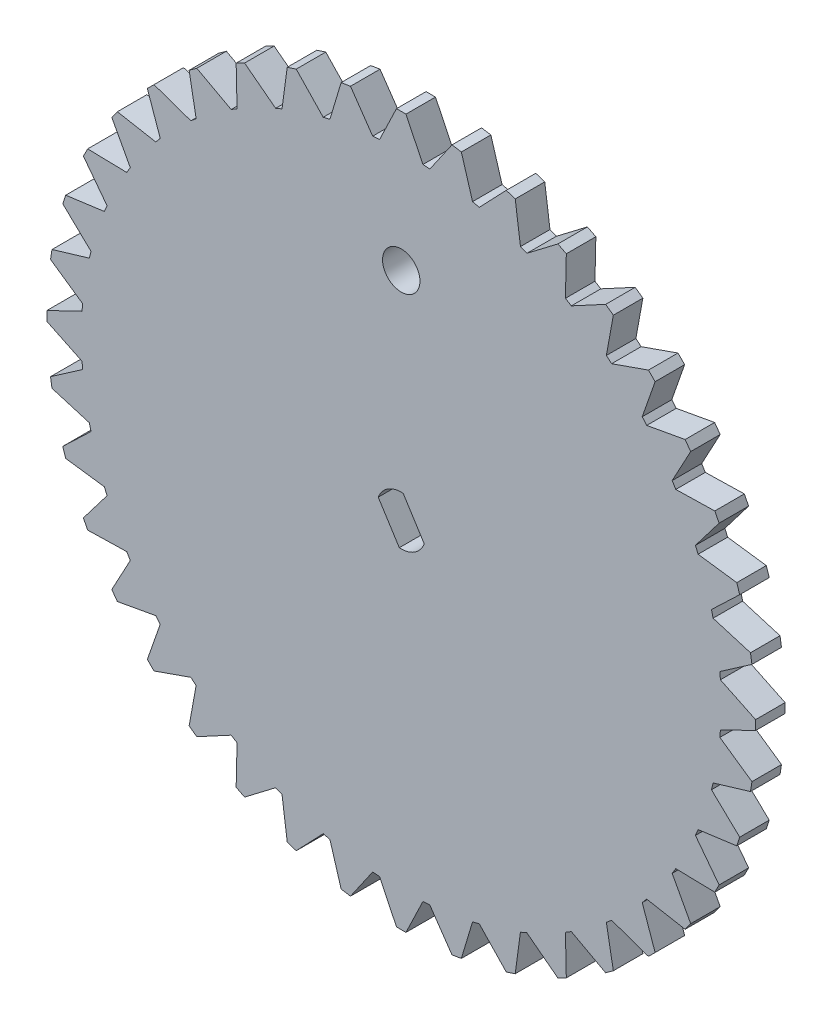
SolidWorks part; units mm, degrees
ref_plane "Front Plane" through (0, 0, 0) normal (0, 0, 1) x (1, 0, 0)
ref_plane "Top Plane" through (0, 0, 0) normal (0, 1, 0) x (1, 0, 0)
ref_plane "Right Plane" through (0, 0, 0) normal (1, 0, 0) x (0, 0, -1)
sketch "Sketch1" plane through (0, 0, 0) normal (0, 0, 1) x (1, 0, 0)
  circle A0 centre (0, 0) radius 32.5
  dimension "D1" = 65
extrude "Boss-Extrude1" add sketch "Sketch1" along normal blind 3
sketch "Sketch2" plane through (0, 0, 3) normal (0, 0, 1) x (1, 0, 0)
  line L210 (0, 37) -> (0, 27.9373) construction
  line L360 (-0.4809, 36) -> (-2.2, 32.4255)
  line L361 (0.4809, 36) -> (2.2, 32.4255)
  line L362 (2.2, 32.4255) -> (-2.2, 32.4255)
  line L489 (-0.4809, 36) -> (0.4809, 36)
  line L690 (6.1066, 35.4815) -> (7.2454, 31.6821)
  line L691 (7.2454, 31.6821) -> (2.8995, 32.3704)
  line L692 (5.1566, 35.632) -> (2.8995, 32.3704)
  line L693 (5.1566, 35.632) -> (6.1066, 35.4815)
  line L694 (11.582, 34.0894) -> (12.1123, 30.1586)
  line L695 (12.1123, 30.1586) -> (7.9277, 31.5183)
  line L696 (10.6672, 34.3866) -> (7.9277, 31.5183)
  line L697 (10.6672, 34.3866) -> (11.582, 34.0894)
  line L698 (16.7722, 31.8579) -> (16.6811, 27.8925)
  line L699 (16.6811, 27.8925) -> (12.7606, 29.8901)
  line L700 (15.9152, 32.2946) -> (12.7606, 29.8901)
  line L701 (15.9152, 32.2946) -> (16.7722, 31.8579)
  line L702 (21.5493, 28.8419) -> (20.839, 24.9396)
  line L703 (20.839, 24.9396) -> (17.2794, 27.5259)
  line L704 (20.7712, 29.4073) -> (17.2794, 27.5259)
  line L705 (20.7712, 29.4073) -> (21.5493, 28.8419)
  line L706 (25.7959, 25.1158) -> (24.4839, 21.3726)
  line L707 (24.4839, 21.3726) -> (21.3726, 24.4839)
  line L708 (25.1158, 25.7959) -> (21.3726, 24.4839)
  line L709 (25.1158, 25.7959) -> (25.7959, 25.1158)
  line L710 (29.4073, 20.7712) -> (27.5259, 17.2794)
  line L711 (27.5259, 17.2794) -> (24.9396, 20.839)
  line L712 (28.8419, 21.5493) -> (24.9396, 20.839)
  line L713 (28.8419, 21.5493) -> (29.4073, 20.7712)
  line L714 (32.2946, 15.9152) -> (29.8901, 12.7606)
  line L715 (29.8901, 12.7606) -> (27.8925, 16.6811)
  line L716 (31.8579, 16.7722) -> (27.8925, 16.6811)
  line L717 (31.8579, 16.7722) -> (32.2946, 15.9152)
  line L718 (34.3866, 10.6672) -> (31.5183, 7.9277)
  line L719 (31.5183, 7.9277) -> (30.1586, 12.1123)
  line L720 (34.0894, 11.582) -> (30.1586, 12.1123)
  line L721 (34.0894, 11.582) -> (34.3866, 10.6672)
  line L722 (35.632, 5.1566) -> (32.3704, 2.8995)
  line L723 (32.3704, 2.8995) -> (31.6821, 7.2454)
  line L724 (35.4815, 6.1066) -> (31.6821, 7.2454)
  line L725 (35.4815, 6.1066) -> (35.632, 5.1566)
  line L726 (36, -0.4809) -> (32.4255, -2.2)
  line L727 (32.4255, -2.2) -> (32.4255, 2.2)
  line L728 (36, 0.4809) -> (32.4255, 2.2)
  line L729 (36, 0.4809) -> (36, -0.4809)
  line L730 (35.4815, -6.1066) -> (31.6821, -7.2454)
  line L731 (31.6821, -7.2454) -> (32.3704, -2.8995)
  line L732 (35.632, -5.1566) -> (32.3704, -2.8995)
  line L733 (35.632, -5.1566) -> (35.4815, -6.1066)
  line L734 (34.0894, -11.582) -> (30.1586, -12.1123)
  line L735 (30.1586, -12.1123) -> (31.5183, -7.9277)
  line L736 (34.3866, -10.6672) -> (31.5183, -7.9277)
  line L737 (34.3866, -10.6672) -> (34.0894, -11.582)
  line L738 (31.8579, -16.7722) -> (27.8925, -16.6811)
  line L739 (27.8925, -16.6811) -> (29.8901, -12.7606)
  line L740 (32.2946, -15.9152) -> (29.8901, -12.7606)
  line L741 (32.2946, -15.9152) -> (31.8579, -16.7722)
  line L742 (28.8419, -21.5493) -> (24.9396, -20.839)
  line L743 (24.9396, -20.839) -> (27.5259, -17.2794)
  line L744 (29.4073, -20.7712) -> (27.5259, -17.2794)
  line L745 (29.4073, -20.7712) -> (28.8419, -21.5493)
  line L746 (25.1158, -25.7959) -> (21.3726, -24.4839)
  line L747 (21.3726, -24.4839) -> (24.4839, -21.3726)
  line L748 (25.7959, -25.1158) -> (24.4839, -21.3726)
  line L749 (25.7959, -25.1158) -> (25.1158, -25.7959)
  line L750 (20.7712, -29.4073) -> (17.2794, -27.5259)
  line L751 (17.2794, -27.5259) -> (20.839, -24.9396)
  line L752 (21.5493, -28.8419) -> (20.839, -24.9396)
  line L753 (21.5493, -28.8419) -> (20.7712, -29.4073)
  line L754 (15.9152, -32.2946) -> (12.7606, -29.8901)
  line L755 (12.7606, -29.8901) -> (16.6811, -27.8925)
  line L756 (16.7722, -31.8579) -> (16.6811, -27.8925)
  line L757 (16.7722, -31.8579) -> (15.9152, -32.2946)
  line L758 (10.6672, -34.3866) -> (7.9277, -31.5183)
  line L759 (7.9277, -31.5183) -> (12.1123, -30.1586)
  line L760 (11.582, -34.0894) -> (12.1123, -30.1586)
  line L761 (11.582, -34.0894) -> (10.6672, -34.3866)
  line L762 (5.1566, -35.632) -> (2.8995, -32.3704)
  line L763 (2.8995, -32.3704) -> (7.2454, -31.6821)
  line L764 (6.1066, -35.4815) -> (7.2454, -31.6821)
  line L765 (6.1066, -35.4815) -> (5.1566, -35.632)
  line L766 (-0.4809, -36) -> (-2.2, -32.4255)
  line L767 (-2.2, -32.4255) -> (2.2, -32.4255)
  line L768 (0.4809, -36) -> (2.2, -32.4255)
  line L769 (0.4809, -36) -> (-0.4809, -36)
  line L770 (-6.1066, -35.4815) -> (-7.2454, -31.6821)
  line L771 (-7.2454, -31.6821) -> (-2.8995, -32.3704)
  line L772 (-5.1566, -35.632) -> (-2.8995, -32.3704)
  line L773 (-5.1566, -35.632) -> (-6.1066, -35.4815)
  line L774 (-11.582, -34.0894) -> (-12.1123, -30.1586)
  line L775 (-12.1123, -30.1586) -> (-7.9277, -31.5183)
  line L776 (-10.6672, -34.3866) -> (-7.9277, -31.5183)
  line L777 (-10.6672, -34.3866) -> (-11.582, -34.0894)
  line L778 (-16.7722, -31.8579) -> (-16.6811, -27.8925)
  line L779 (-16.6811, -27.8925) -> (-12.7606, -29.8901)
  line L780 (-15.9152, -32.2946) -> (-12.7606, -29.8901)
  line L781 (-15.9152, -32.2946) -> (-16.7722, -31.8579)
  line L782 (-21.5493, -28.8419) -> (-20.839, -24.9396)
  line L783 (-20.839, -24.9396) -> (-17.2794, -27.5259)
  line L784 (-20.7712, -29.4073) -> (-17.2794, -27.5259)
  line L785 (-20.7712, -29.4073) -> (-21.5493, -28.8419)
  line L786 (-25.7959, -25.1158) -> (-24.4839, -21.3726)
  line L787 (-24.4839, -21.3726) -> (-21.3726, -24.4839)
  line L788 (-25.1158, -25.7959) -> (-21.3726, -24.4839)
  line L789 (-25.1158, -25.7959) -> (-25.7959, -25.1158)
  line L790 (-29.4073, -20.7712) -> (-27.5259, -17.2794)
  line L791 (-27.5259, -17.2794) -> (-24.9396, -20.839)
  line L792 (-28.8419, -21.5493) -> (-24.9396, -20.839)
  line L793 (-28.8419, -21.5493) -> (-29.4073, -20.7712)
  line L794 (-32.2946, -15.9152) -> (-29.8901, -12.7606)
  line L795 (-29.8901, -12.7606) -> (-27.8925, -16.6811)
  line L796 (-31.8579, -16.7722) -> (-27.8925, -16.6811)
  line L797 (-31.8579, -16.7722) -> (-32.2946, -15.9152)
  line L798 (-34.3866, -10.6672) -> (-31.5183, -7.9277)
  line L799 (-31.5183, -7.9277) -> (-30.1586, -12.1123)
  line L800 (-34.0894, -11.582) -> (-30.1586, -12.1123)
  line L801 (-34.0894, -11.582) -> (-34.3866, -10.6672)
  line L802 (-35.632, -5.1566) -> (-32.3704, -2.8995)
  line L803 (-32.3704, -2.8995) -> (-31.6821, -7.2454)
  line L804 (-35.4815, -6.1066) -> (-31.6821, -7.2454)
  line L805 (-35.4815, -6.1066) -> (-35.632, -5.1566)
  line L806 (-36, 0.4809) -> (-32.4255, 2.2)
  line L807 (-32.4255, 2.2) -> (-32.4255, -2.2)
  line L808 (-36, -0.4809) -> (-32.4255, -2.2)
  line L809 (-36, -0.4809) -> (-36, 0.4809)
  line L810 (-35.4815, 6.1066) -> (-31.6821, 7.2454)
  line L811 (-31.6821, 7.2454) -> (-32.3704, 2.8995)
  line L812 (-35.632, 5.1566) -> (-32.3704, 2.8995)
  line L813 (-35.632, 5.1566) -> (-35.4815, 6.1066)
  line L814 (-34.0894, 11.582) -> (-30.1586, 12.1123)
  line L815 (-30.1586, 12.1123) -> (-31.5183, 7.9277)
  line L816 (-34.3866, 10.6672) -> (-31.5183, 7.9277)
  line L817 (-34.3866, 10.6672) -> (-34.0894, 11.582)
  line L818 (-31.8579, 16.7722) -> (-27.8925, 16.6811)
  line L819 (-27.8925, 16.6811) -> (-29.8901, 12.7606)
  line L820 (-32.2946, 15.9152) -> (-29.8901, 12.7606)
  line L821 (-32.2946, 15.9152) -> (-31.8579, 16.7722)
  line L822 (-28.8419, 21.5493) -> (-24.9396, 20.839)
  line L823 (-24.9396, 20.839) -> (-27.5259, 17.2794)
  line L824 (-29.4073, 20.7712) -> (-27.5259, 17.2794)
  line L825 (-29.4073, 20.7712) -> (-28.8419, 21.5493)
  line L826 (-25.1158, 25.7959) -> (-21.3726, 24.4839)
  line L827 (-21.3726, 24.4839) -> (-24.4839, 21.3726)
  line L828 (-25.7959, 25.1158) -> (-24.4839, 21.3726)
  line L829 (-25.7959, 25.1158) -> (-25.1158, 25.7959)
  line L830 (-20.7712, 29.4073) -> (-17.2794, 27.5259)
  line L831 (-17.2794, 27.5259) -> (-20.839, 24.9396)
  line L832 (-21.5493, 28.8419) -> (-20.839, 24.9396)
  line L833 (-21.5493, 28.8419) -> (-20.7712, 29.4073)
  line L834 (-15.9152, 32.2946) -> (-12.7606, 29.8901)
  line L835 (-12.7606, 29.8901) -> (-16.6811, 27.8925)
  line L836 (-16.7722, 31.8579) -> (-16.6811, 27.8925)
  line L837 (-16.7722, 31.8579) -> (-15.9152, 32.2946)
  line L838 (-10.6672, 34.3866) -> (-7.9277, 31.5183)
  line L839 (-7.9277, 31.5183) -> (-12.1123, 30.1586)
  line L840 (-11.582, 34.0894) -> (-12.1123, 30.1586)
  line L841 (-11.582, 34.0894) -> (-10.6672, 34.3866)
  line L842 (-5.1566, 35.632) -> (-2.8995, 32.3704)
  line L843 (-2.8995, 32.3704) -> (-7.2454, 31.6821)
  line L844 (-6.1066, 35.4815) -> (-7.2454, 31.6821)
  line L845 (-6.1066, 35.4815) -> (-5.1566, 35.632)
  circle A5 centre (0, 0) radius 32.5 construction
  arc A6 (-32.9057, -16.918) -> (-36.778, 4.0467) centre (0, 0) ccw construction
  dimension "D4" = 2.2
  dimension "D5" = 1
  dimension "D3" = 2.2
  dimension "D2" = 37
extrude "Boss-Extrude6" add sketch "Sketch2" against normal up to surface (3 mm away) up to face at (32.5, 0, 0)
sketch "Sketch3" plane through (0, 0, 3) normal (0, 0, 1) x (1, 0, 0)
  line L7 (-2.337, 0.8878) -> (-0.198, -2.4921)
  line L8 (0.198, 2.4921) -> (2.337, -0.8878)
  line L9 (-0.198, -2.4921) -> (-2.337, 0.8878) construction
  circle A4 centre (0, 0) radius 2.5 construction
  arc A5 (0.198, 2.4921) -> (-2.337, 0.8878) centre (0, 0) ccw
  arc A6 (-0.198, -2.4921) -> (2.337, -0.8878) centre (0, 0) ccw
extrude "Cut-Extrude1" cut sketch "Sketch3" against normal up to surface (3 mm away) up to face at (0, 0, 0)
sketch "Sketch5" plane through (0, 0, 0) normal (0, 0, -1) x (-1, 0, 0)
  line L0 (-0.198, 2.4921) -> (-2.337, -0.8878)
  line L1 (0.198, -2.4921) -> (2.337, 0.8878)
  circle A0 centre (0, 0) radius 7
  arc A1 (2.337, 0.8878) -> (-0.198, 2.4921) centre (0, 0) ccw
  arc A2 (-2.337, -0.8878) -> (0.198, -2.4921) centre (0, 0) ccw
  dimension "D1" = 14
extrude "Boss-Extrude7" add sketch "Sketch5" along normal up to surface (3 mm away)
sketch "Sketch7" plane through (0, 0, 3) normal (0, 0, 1) x (1, 0, 0)
  line L0 (0, 0) -> (0, 22) construction
  circle A0 centre (0, 22) radius 1.9
  dimension "D2" = 3.8
  dimension "D1" = 22
extrude "Cut-Extrude2" cut sketch "Sketch7" against normal up to surface (3 mm away) contours A0 up to face at (7, 0, 0)
